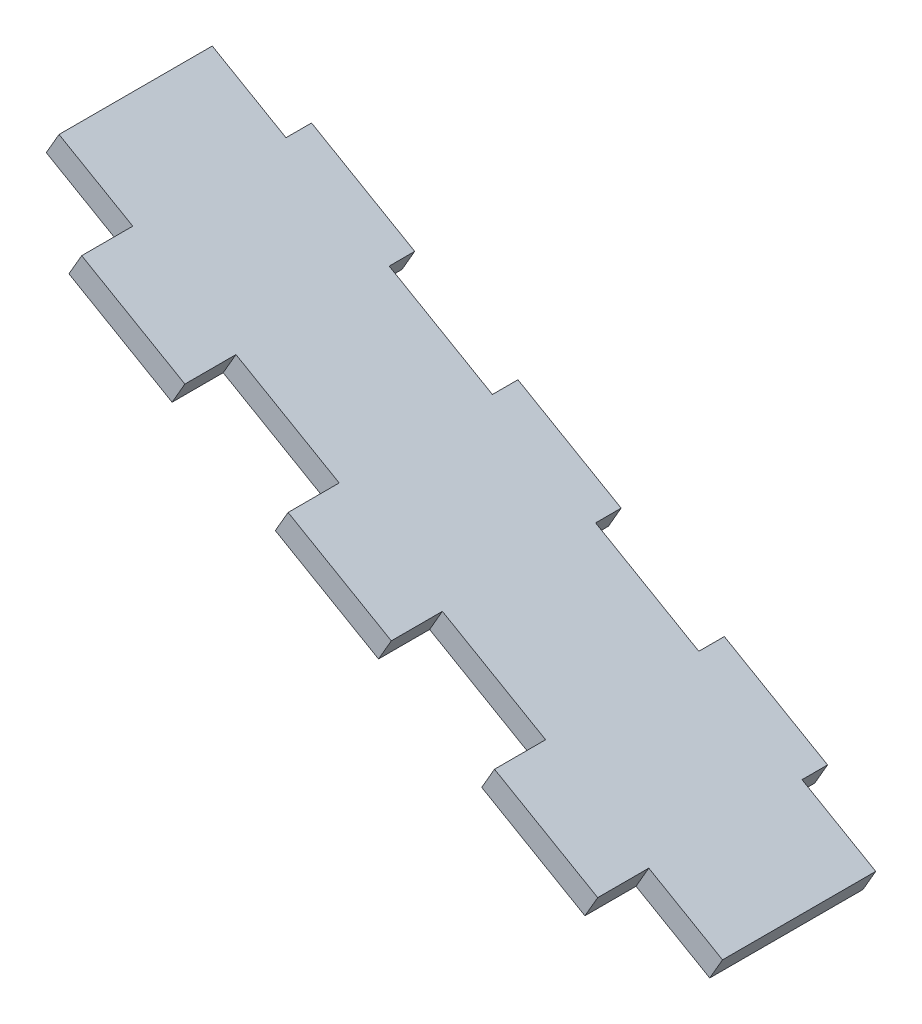
SolidWorks part; units mm, degrees
ref_plane "Plan de face" through (0, 0, 0) normal (0, 0, 1) x (1, 0, 0)
ref_plane "Plan de dessus" through (0, 0, 0) normal (0, 1, 0) x (1, 0, 0)
ref_plane "Plan de droite" through (0, 0, 0) normal (1, 0, 0) x (0, 0, -1)
sketch "Esquisse1" plane through (0, 0, 0) normal (0, 0, 1) x (1, 0, 0)
  line L0 (-148.314, -76.8873) -> (7.5706, -166.8873) construction
  line L1 (-153.5637, -85.9801) -> (-138.0637, -59.1333) construction
  line L2 (2.3209, -175.9801) -> (17.8209, -149.1333) construction
  line L3 (-178.5574, -82.5203) -> (17.3271, -195.6143) construction
  line L4 (6.0706, -169.4854) -> (-149.814, -79.4854)
  line L5 (6.0706, -169.4854) -> (9.0706, -164.2893)
  line L6 (-149.814, -79.4854) -> (-146.814, -74.2893)
  line L7 (9.0706, -164.2893) -> (-146.814, -74.2893)
  line L8 (6.0706, -169.4854) -> (-146.814, -74.2893) construction
  line L9 (-149.814, -79.4854) -> (9.0706, -164.2893) construction
  point P8 (-70.3717, -121.8873)
  point P9 (-70.3717, -121.8873)
  dimension "D1" = 20
  dimension "D2" = 6
extrude "Boss.-Extru.1" add sketch "Esquisse1" along normal up to surface (36 mm away)
sketch "Esquisse3" plane through (0, 0, 0) normal (0, 0, -1) x (-1, 0, 0)
  line L0 (8.2499, -154.2893) -> (11.2499, -159.4854)
  line L1 (-9.0706, -164.2893) -> (146.814, -74.2893) construction
  line L2 (149.814, -79.4854) -> (-6.0706, -169.4854) construction
  line L3 (11.2499, -159.4854) -> (35.4986, -145.4854)
  line L4 (35.4986, -145.4854) -> (32.4986, -140.2893)
  line L5 (32.4986, -140.2893) -> (8.2499, -154.2893)
  line L6 (68.8717, -119.2893) -> (71.8717, -124.4854) construction
  line L7 (68.8717, -119.2893) -> (71.8717, -124.4854)
  line L8 (83.996, -117.4854) -> (59.7473, -131.4854)
  line L9 (59.7473, -131.4854) -> (56.7473, -126.2893)
  line L10 (56.7473, -126.2893) -> (80.996, -112.2893)
  line L11 (108.2448, -103.4854) -> (105.2448, -98.2893)
  line L12 (132.4935, -89.4854) -> (108.2448, -103.4854)
  line L13 (129.4935, -84.2893) -> (132.4935, -89.4854)
  line L14 (105.2448, -98.2893) -> (129.4935, -84.2893)
  line L15 (83.996, -117.4854) -> (80.996, -112.2893)
  line M10 (-6.0706, -169.4854) -> (149.814, -79.4854)
  line M12 (146.814, -74.2893) -> (-9.0706, -164.2893)
  dimension "D1" = 14
  dimension "D2" = 28
  dimension "D3" = 28
extrude "Boss.-Extru.2" add sketch "Esquisse3" along normal blind 6 and the other way blind 48 contours L4 L0 M10 M12 | L9 L7 M10 M12 | L15 L7 M10 M12 | L13 L11 M12 M10
equation "\"D2@Esquisse3\"=2*\"D1@Esquisse3\""
equation "\"D3@Esquisse3\"=2*\"D1@Esquisse3\""
